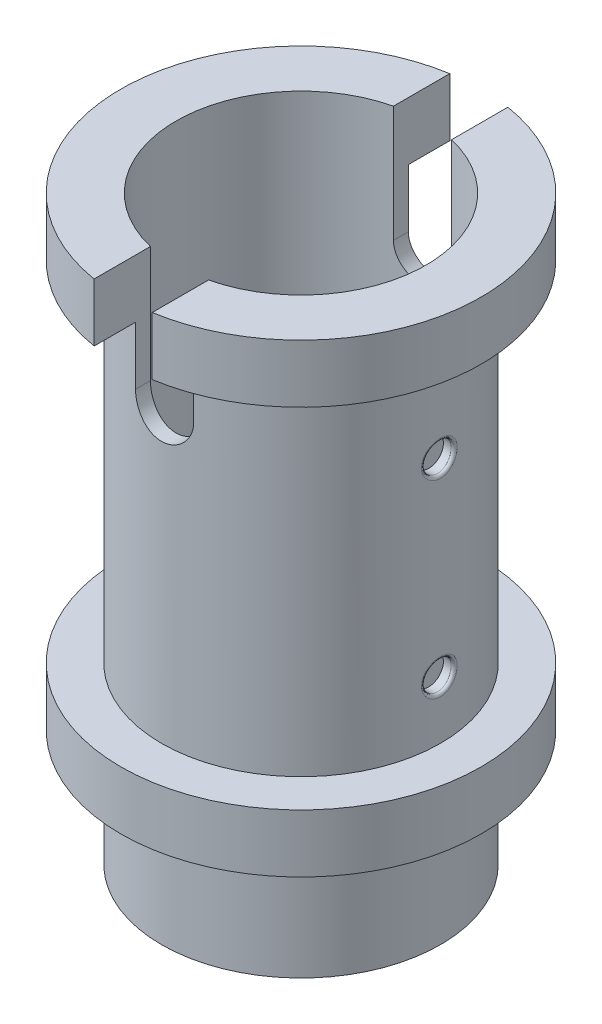
SolidWorks part; units mm, degrees
ref_plane "Front Plane" through (0, 0, 0) normal (0, 0, 1) x (1, 0, 0)
ref_plane "Top Plane" through (0, 0, 0) normal (0, 1, 0) x (1, 0, 0)
ref_plane "Right Plane" through (0, 0, 0) normal (1, 0, 0) x (0, 0, -1)
sketch "Sketch2" plane through (0, 0, 0) normal (0, 1, 0) x (1, 0, 0)
  circle A0 centre (0, 0) radius 2.4
  dimension "D1" = 4.8
extrude "Boss-Extrude1" add sketch "Sketch2" along normal blind 2
sketch "Sketch3" plane through (0, 2, 0) normal (0, 1, 0) x (1, 0, 0)
  circle A0 centre (0, 0) radius 3.1
extrude "Boss-Extrude2" add sketch "Sketch3" along normal blind 1
sketch "Sketch4" plane through (0, 3, 0) normal (0, 1, 0) x (1, 0, 0)
  circle A0 centre (0, 0) radius 2.4
  dimension "D1" = 4.8
extrude "Boss-Extrude3" add sketch "Sketch4" along normal blind 6
sketch "Sketch5" plane through (0, 9, 0) normal (0, 1, 0) x (1, 0, 0)
  circle A0 centre (0, 0) radius 3.1
  dimension "D1" = 6.2
extrude "Boss-Extrude4" add sketch "Sketch5" along normal blind 1
sketch "Sketch6" plane through (0, 0, 0) normal (0, 0, 1) x (1, 0, 0)
  line L0 (0, 10) -> (0, 8) construction
  line L1 (3.1, 10) -> (-3.1, 10) construction
  line L2 (0.5, 10) -> (0.5, 8)
  line L3 (-0.5, 10) -> (-0.5, 8)
  arc A0 (0.5, 10) -> (-0.5, 10) centre (0, 10) ccw
  arc A1 (-0.5, 8) -> (0.5, 8) centre (0, 8) ccw
  point P5 (0, 9)
  dimension "D1" = 2
  dimension "D2" = 1
extrude "Cut-Extrude1" cut sketch "Sketch6" against normal through all both and the other way through all
ref_plane "Plane1" through (2.4, 0, 0) normal (1, 0, 0) x (0, 0, -1)
sketch "Sketch7" plane through (2.4, 0, 0) normal (1, 0, 0) x (0, 0, -1)
  circle A0 centre (0, 7.2481) radius 0.25
  circle A1 centre (0, 3.9943) radius 0.25
  dimension "D1" = 0.5
  dimension "D2" = 0.5
extrude "Cut-Extrude2" cut sketch "Sketch7" against normal blind 0.2
fillet "Fillet1" radius 0.05 1 edges at (2.3876, 7.3041, 0.2437)
fillet "Fillet2" radius 0.05 1 edges at (2.3876, 4.0503, 0.2437)
sketch "Sketch9" plane through (0, 0, 0) normal (0, -1, 0) x (-1, 0, 0)
  circle A0 centre (0, 0) radius 2.15
  dimension "D1" = 4.3
extrude "Cut-Extrude3" cut sketch "Sketch9" against normal through all both and the other way through all
